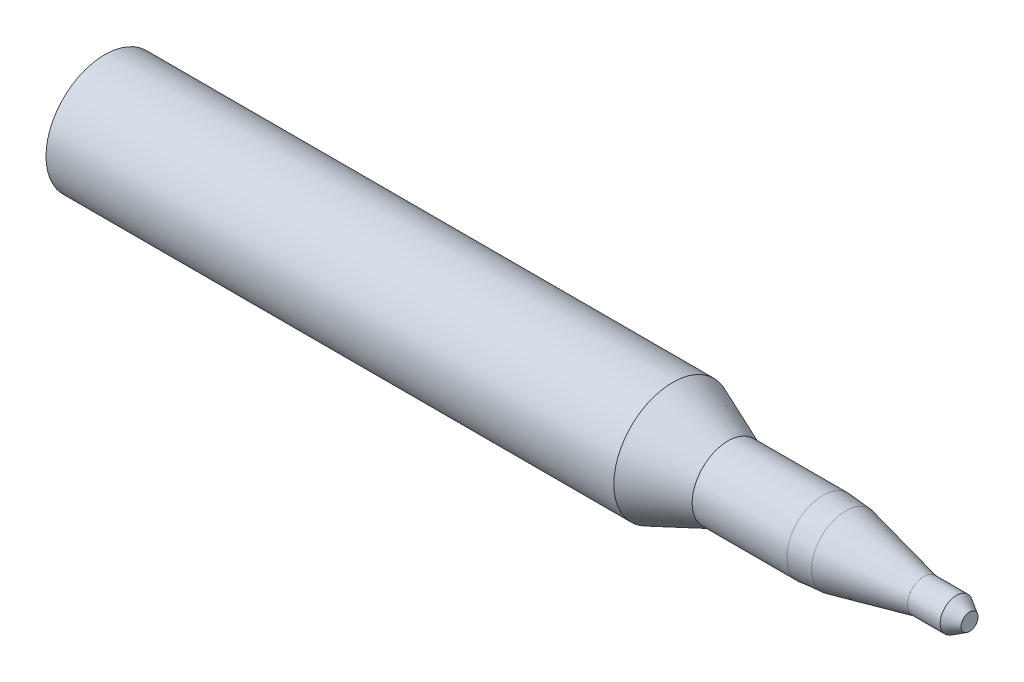
SolidWorks part; units mm, degrees
ref_plane "Front Plane" through (0, 0, 0) normal (0, 0, 1) x (1, 0, 0)
ref_plane "Top Plane" through (0, 0, 0) normal (0, 1, 0) x (1, 0, 0)
ref_plane "Right Plane" through (0, 0, 0) normal (1, 0, 0) x (0, 0, -1)
sketch "Sketch2" plane through (0, 0, 0) normal (0, 0, 1) x (1, 0, 0)
  line L0 (0, 0) -> (1325, 0)
  line L1 (1325, 0) -> (1325, 13)
  line L3 (1285, 25) -> (1255, 25)
  line L4 (1255, 25) -> (1135, 52.0637)
  line L6 (1100, 55) -> (955, 55)
  line L7 (955, 55) -> (870, 90)
  line L8 (870, 90) -> (0, 90)
  line L9 (0, 90) -> (0, 0)
  line L10 (1100, 55) -> (1135, 52.0637)
  line L11 (1325, 13) -> (1305, 25)
  line L12 (1305, 25) -> (1285, 25)
  dimension "D1" = 1325
  dimension "D2" = 870
  dimension "D3" = 85
  dimension "D4" = 13
  dimension "D5" = 145
  dimension "D6" = 30
  dimension "D7" = 25
  dimension "D8" = 35
  dimension "D9" = 120
  dimension "D10" = 20
  dimension "D11" = 55
  dimension "D12" = 90
revolve "Revolve1" add sketch "Sketch2" angle 360 about L0
